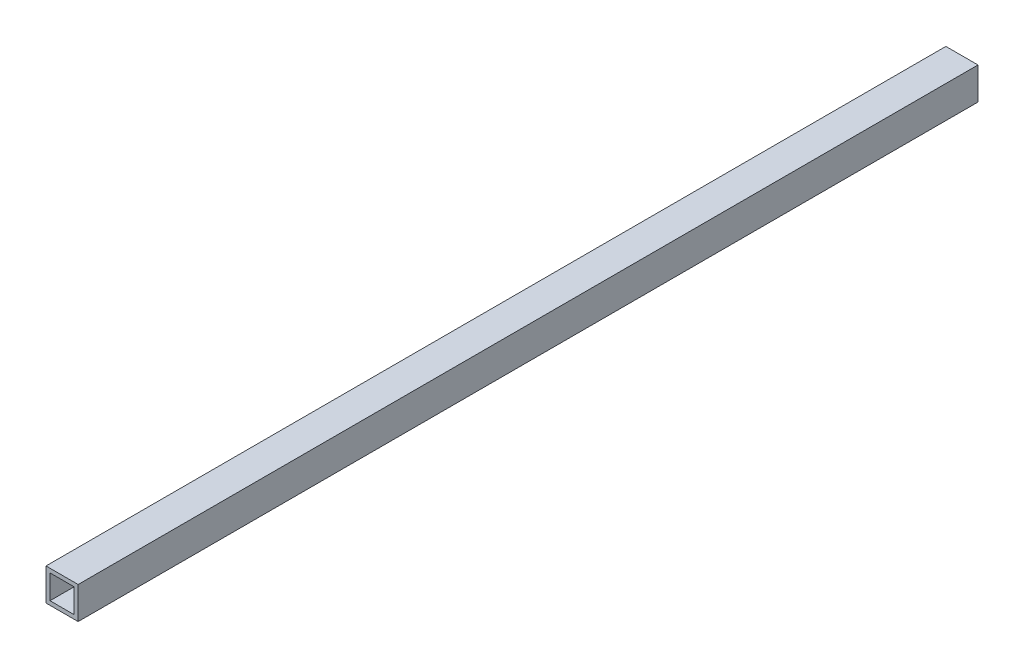
SolidWorks part; units mm, degrees
material "1060 Alloy"
ref_plane "Front Plane" through (0, 0, 0) normal (0, 0, 1) x (1, 0, 0)
ref_plane "Top Plane" through (0, 0, 0) normal (0, 1, 0) x (1, 0, 0)
ref_plane "Right Plane" through (0, 0, 0) normal (1, 0, 0) x (0, 0, -1)
sketch "Sketch1" plane through (0, 0, 0) normal (0, 0, 1) x (1, 0, 0)
  line L1 (0, 0) -> (25.4, 0)
  line L2 (0, 0) -> (0, 25.4)
  line L3 (0, 25.4) -> (25.4, 25.4)
  line L4 (25.4, 0) -> (25.4, 25.4)
  line L5 (3.175, 3.175) -> (22.225, 3.175)
  line L6 (3.175, 3.175) -> (3.175, 22.225)
  line L7 (3.175, 22.225) -> (22.225, 22.225)
  line L8 (22.225, 3.175) -> (22.225, 22.225)
  dimension "D1" = 25.4
  dimension "D2" = 25.4
  dimension "D3" = 3.175
  dimension "D4" = 3.175
  dimension "D5" = 3.175
  dimension "D6" = 3.175
extrude "Boss-Extrude1" add sketch "Sketch1" along normal blind 711.2
